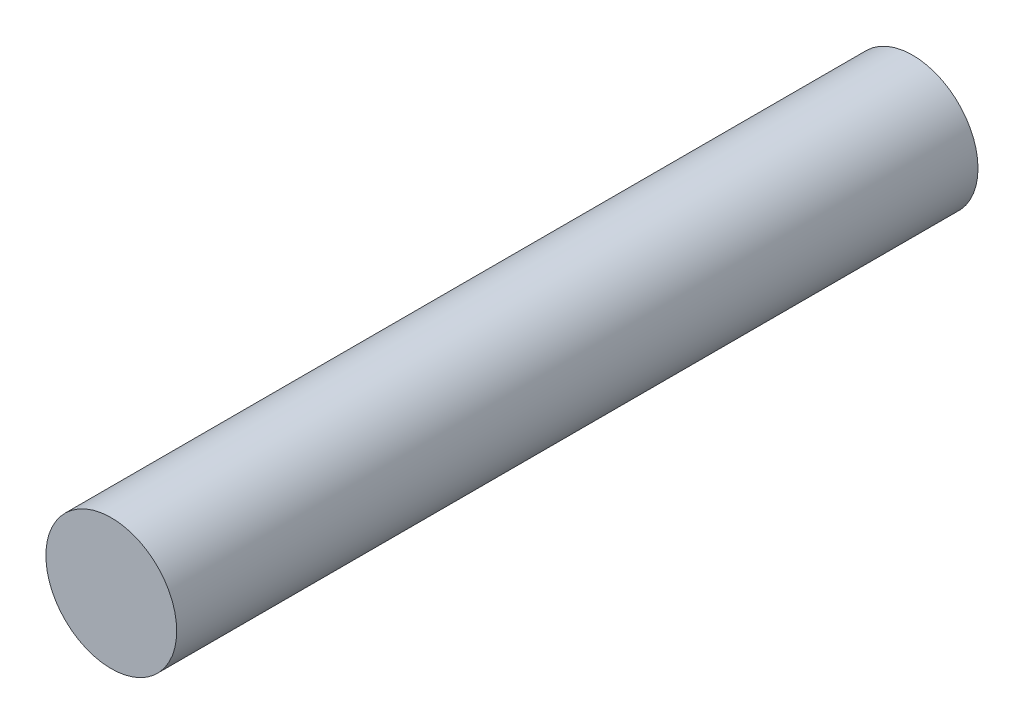
SolidWorks part; units mm, degrees
ref_plane "Front Plane" through (0, 0, 0) normal (0, 0, 1) x (1, 0, 0)
ref_plane "Top Plane" through (0, 0, 0) normal (0, 1, 0) x (1, 0, 0)
ref_plane "Right Plane" through (0, 0, 0) normal (1, 0, 0) x (0, 0, -1)
sketch "Sketch1" plane through (0, 0, 0) normal (0, 0, 1) x (1, 0, 0)
  circle A0 centre (0, 0) radius 4
extrude "Boss-Extrude1" add sketch "Sketch1" along normal blind 49
